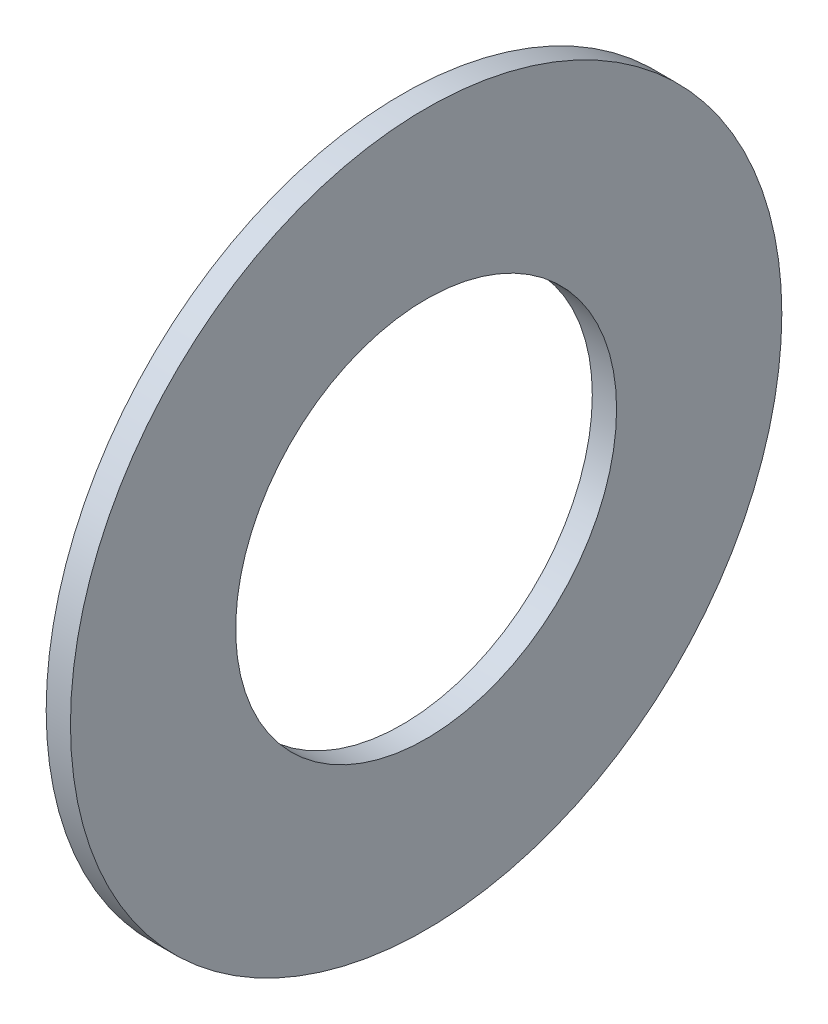
SolidWorks part; units mm, degrees
ref_plane "Front Plane" through (0, 0, 0) normal (0, 0, 1) x (1, 0, 0)
ref_plane "Top Plane" through (0, 0, 0) normal (0, 1, 0) x (1, 0, 0)
ref_plane "Right Plane" through (0, 0, 0) normal (1, 0, 0) x (0, 0, -1)
sketch "Sketch1" plane through (0, 0, 0) normal (1, 0, 0) x (0, 0, -1)
  line L0 (6.35, 0) -> (-6.35, 0) construction
  circle A0 centre (0, 0) radius 11.9062 construction
  circle A1 centre (0, 0) radius 6.3754 construction
  circle A2 centre (0, 0) radius 6.35
  point P9 (0, 0)
  dimension "OD" = 23.8125
  dimension "ID" = 12.7508
  dimension "For Shaft Diameter" = 12.7
sketch "Sketch2" plane through (0, 0, 0) normal (0, 0, 1) x (1, 0, 0)
  line L0 (0.4064, 0) -> (-0.4064, 0) construction
  line L2 (0.4064, -11.9062) -> (-0.4064, -11.9062) construction
  line L3 (0.4064, -11.9062) -> (0.4064, 11.9062) construction
  line L4 (0.4064, 11.9062) -> (-0.4064, 11.9062) construction
  line L5 (-0.4064, -11.9062) -> (-0.4064, 11.9062) construction
  line L6 (0, 11.9062) -> (0, -11.9062) construction
  line L7 (0.4064, 0) -> (-0.4064, 0) construction
  line L8 (0, -11.9062) -> (0, 11.9062) construction
  point P0 (0, 0)
  point P4 (0, 0)
  dimension "Thickness" = 0.8128
  dimension "D1" = 23.8125
sketch "Sketch5" plane through (0, 0, 0) normal (1, 0, 0) x (0, 0, -1)
  circle A0 centre (0, 0) radius 6.3754 construction
  circle A1 centre (0, 0) radius 11.9062 construction
  circle A3 centre (0, 0) radius 6.3754
  circle A5 centre (0, 0) radius 11.9062
extrude "Boss-Extrude1" add sketch "Sketch5" along normal mid plane 0.8128
equation "\"D1@Boss-Extrude1\"= \"Thickness@Sketch2\""
equation "\"D1@Sketch2\"=\"OD@Sketch1\""
